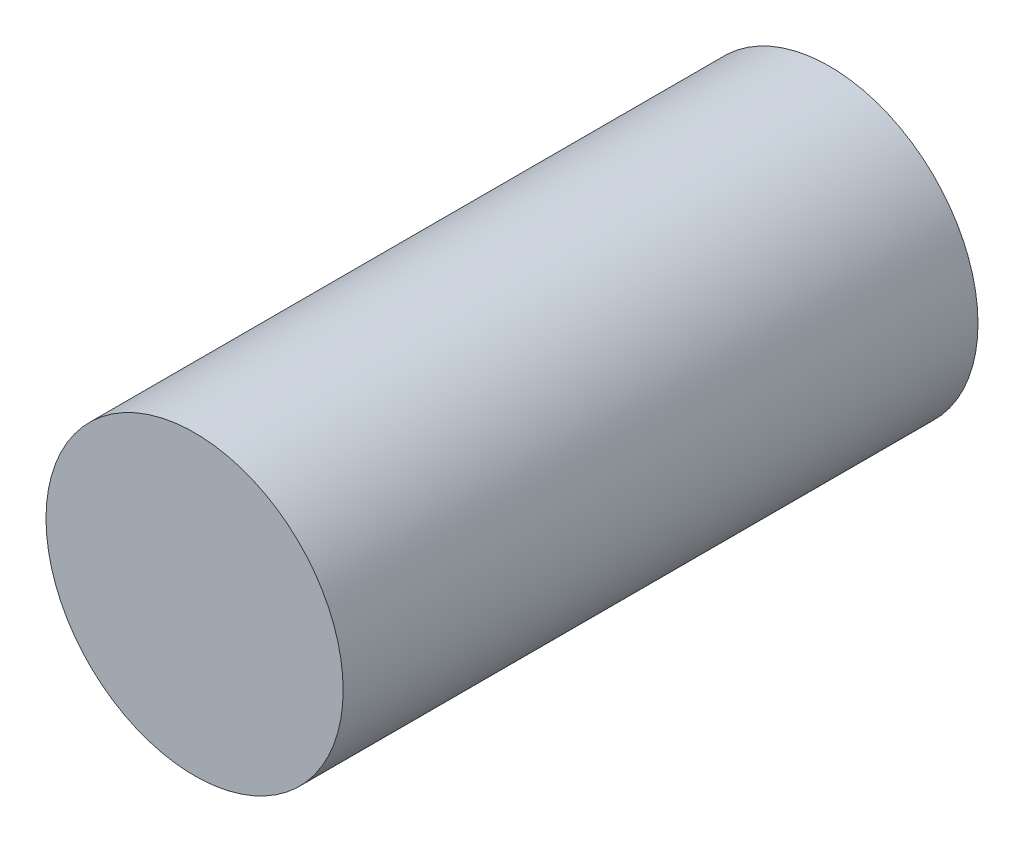
SolidWorks part; units mm, degrees
ref_plane "Plan de face" through (0, 0, 0) normal (0, 0, 1) x (1, 0, 0)
ref_plane "Plan de dessus" through (0, 0, 0) normal (0, 1, 0) x (1, 0, 0)
ref_plane "Plan de droite" through (0, 0, 0) normal (1, 0, 0) x (0, 0, -1)
sketch "Esquisse1" plane through (0, 0, 0) normal (0, 0, 1) x (1, 0, 0)
  circle A0 centre (0, 0) radius 11
  dimension "D1" = 22
extrude "Boss.-Extru.1" add sketch "Esquisse1" along normal blind 47
